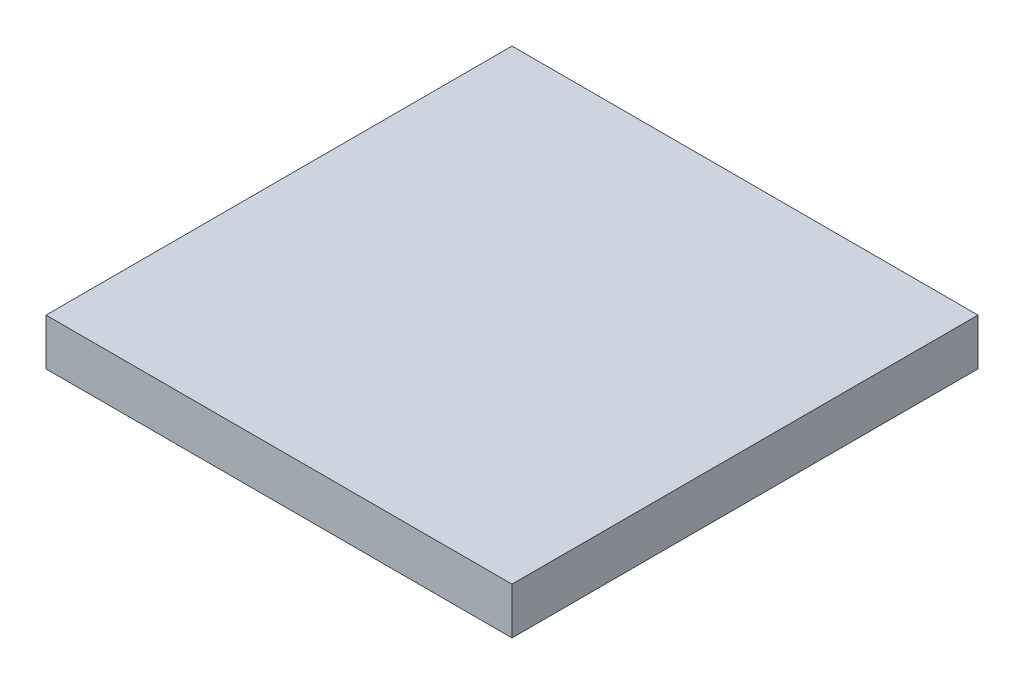
SolidWorks part; units mm, degrees
ref_plane "Front Plane" through (0, 0, 0) normal (0, 0, 1) x (1, 0, 0)
ref_plane "Top Plane" through (0, 0, 0) normal (0, 1, 0) x (1, 0, 0)
ref_plane "Right Plane" through (0, 0, 0) normal (1, 0, 0) x (0, 0, -1)
sketch "Sketch1" plane through (0, 0, 0) normal (0, 1, 0) x (1, 0, 0)
  line L1 (0, 0) -> (5, 0)
  line L2 (0, 0) -> (0, 5)
  line L3 (0, 5) -> (5, 5)
  line L4 (5, 0) -> (5, 5)
  line L5 (0, 0) -> (5, 5) construction
  line L6 (0, 5) -> (5, 0) construction
  point P4 (2.5, 2.5)
  dimension "D1" = 5
  dimension "D2" = 5
extrude "Boss-Extrude1" add sketch "Sketch1" along normal blind 0.5
